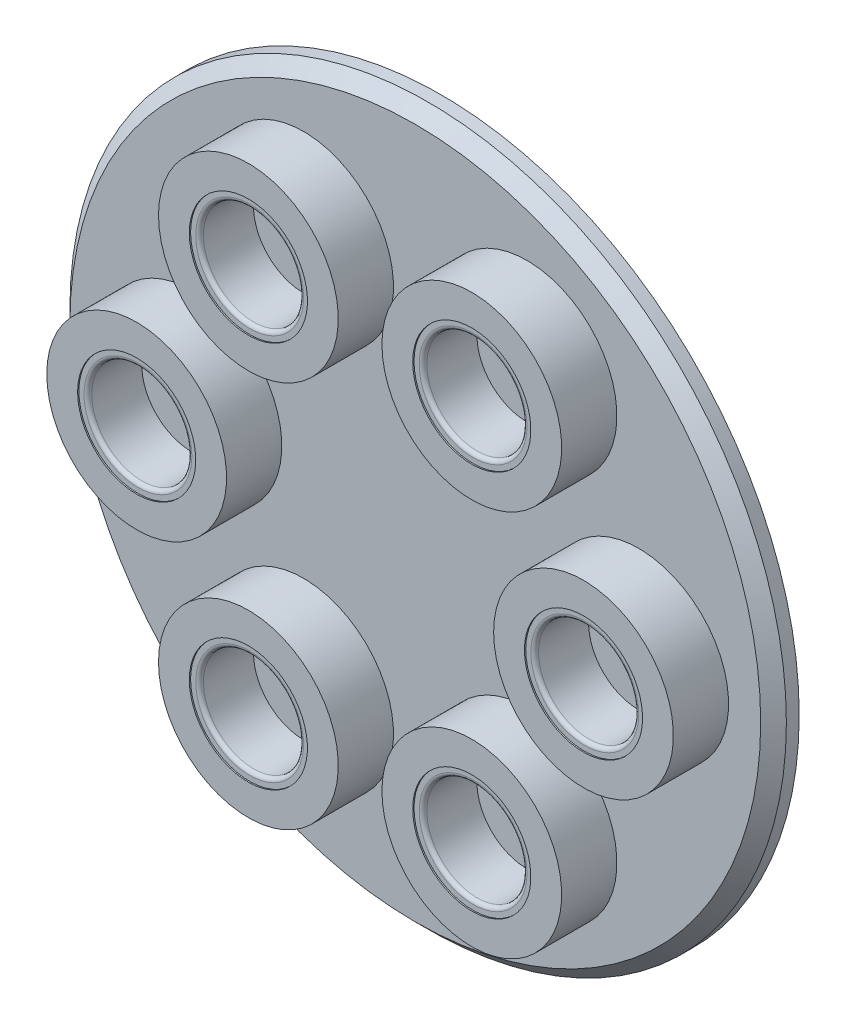
SolidWorks part; units mm, degrees
ref_plane "Front Plane" through (0, 0, 0) normal (0, 0, 1) x (1, 0, 0)
ref_plane "Top Plane" through (0, 0, 0) normal (0, 1, 0) x (1, 0, 0)
ref_plane "Right Plane" through (0, 0, 0) normal (1, 0, 0) x (0, 0, -1)
sketch "Sketch1" plane through (0, 0, 0) normal (0, 0, 1) x (1, 0, 0)
  circle A0 centre (0, 0) radius 27.9
  dimension "D1" = 55.8
extrude "Boss-Extrude1" add sketch "Sketch1" along normal blind 2
chamfer "Chamfer1" distance 1 angle 45 1 edges at (27.9, 0, 2)
sketch "Sketch2" plane through (0, 0, 2) normal (0, 0, 1) x (1, 0, 0)
  line L0 (0, 0) -> (0, 26.9) construction
  line L1 (0, 0) -> (23.2961, -13.45) construction
  line L2 (0, 0) -> (-23.2961, -13.45) construction
  line L3 (0, 0) -> (8.7, 15.0688) construction
  line L4 (0, 0) -> (8.7, -15.0688) construction
  circle A0 centre (-8.7, 15.0688) radius 7
  circle A1 centre (8.7, 15.0688) radius 7
  circle A2 centre (0, 0) radius 17.4 construction
  circle A3 centre (0, 0) radius 26.9 construction
  circle A4 centre (-8.7, 15.0688) radius 4.6
  circle A5 centre (8.7, 15.0688) radius 4.6
  circle A6 centre (17.4, 0) radius 4.6
  circle A7 centre (17.4, 0) radius 7
  circle A8 centre (8.7, -15.0688) radius 7
  circle A9 centre (8.7, -15.0688) radius 4.6
  circle A10 centre (-8.7, -15.0688) radius 4.6
  circle A11 centre (-8.7, -15.0688) radius 7
  circle A12 centre (-17.4, 0) radius 7
  circle A13 centre (-17.4, 0) radius 4.6
  dimension "D1" = 14
  dimension "D4" = 34.8
  dimension "D5" = 9.2
  dimension "D2" = 8.7
  dimension "D3" = 17.4
  dimension "D7" = 120
  dimension "D6" = 3
extrude "Boss-Extrude2" add sketch "Sketch2" along normal blind 4.3
sketch "Sketch3" plane through (0, 0, 2) normal (0, 0, 1) x (1, 0, 0)
  line L0 (0, 0) -> (0, 26.9) construction
  line L1 (0, 0) -> (23.2961, -13.45) construction
  line L2 (0, 0) -> (-23.2961, -13.45) construction
  line L3 (0, 0) -> (8.7, 15.0688) construction
  line L4 (0, 0) -> (8.7, -15.0688) construction
  line L5 (0, 0) -> (23.2961, -13.45) construction
  line L6 (0, 0) -> (-23.2961, -13.45) construction
  line L7 (0, 0) -> (8.7, 15.0688) construction
  circle A0 centre (8.7, 15.0688) radius 4.6
  circle A1 centre (-8.7, 15.0688) radius 4.6
  circle A2 centre (-8.7, 15.0688) radius 4.6 construction
  circle A3 centre (8.7, 15.0688) radius 4.6 construction
  circle A4 centre (0, 0) radius 26.9 construction
  circle A5 centre (17.4, 0) radius 4.6
  circle A6 centre (8.7, -15.0688) radius 4.6
  circle A7 centre (-8.7, -15.0688) radius 4.6
  circle A8 centre (-17.4, 0) radius 4.6
  circle A9 centre (-8.7, 15.0688) radius 3.9
  circle A10 centre (8.7, 15.0688) radius 3.9
  circle A11 centre (17.4, 0) radius 3.9
  circle A12 centre (8.7, -15.0688) radius 3.9
  circle A13 centre (-8.7, -15.0688) radius 3.9
  circle A14 centre (-17.4, 0) radius 3.9
  dimension "D1" = 3
  dimension "D3" = 7.8
  dimension "D4" = 3
  dimension "D2" = 120
extrude "Boss-Extrude4" add sketch "Sketch3" along normal blind 4.2
fillet "Fillet1" radius 0.3 6 edges at (-13.5, 0, 6.2) (-4.8, -15.0688, 6.2) (12.6, -15.0688, 6.2) (21.3, 0, 6.2) (12.6, 15.0688, 6.2) (-4.8, 15.0688, 6.2)
